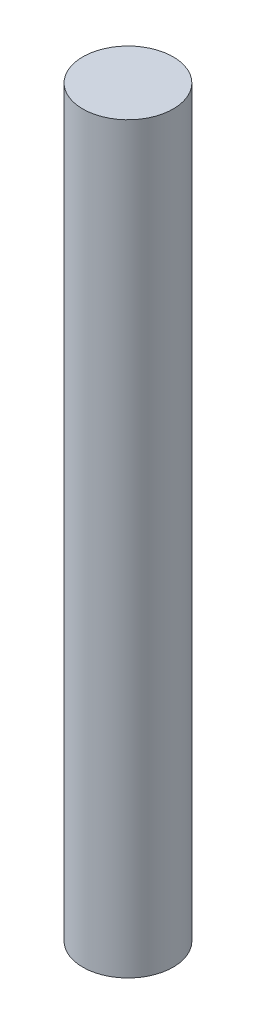
SolidWorks part; units mm, degrees
material "Polylactide (PLA)"
ref_plane "Front Plane" through (0, 0, 0) normal (0, 0, 1) x (1, 0, 0)
ref_plane "Top Plane" through (0, 0, 0) normal (0, 1, 0) x (1, 0, 0)
ref_plane "Right Plane" through (0, 0, 0) normal (1, 0, 0) x (0, 0, -1)
sketch "Sketch1" plane through (0, 0, 0) normal (0, 1, 0) x (1, 0, 0)
  circle A0 centre (0, 0) radius 2.25
  dimension "D1" = 4.5
extrude "Boss-Extrude1" add sketch "Sketch1" along normal blind 37
